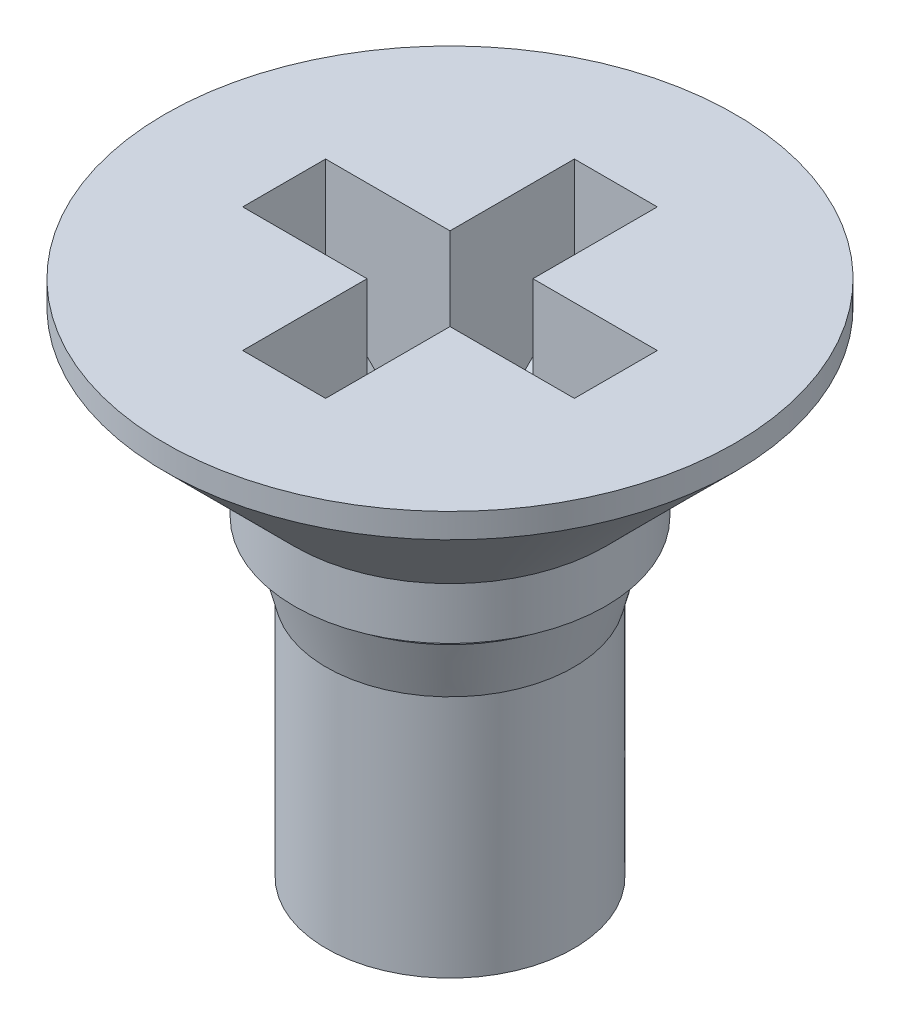
SolidWorks part; units mm, degrees
ref_plane "Vorderseite" through (0, 0, 0) normal (0, 0, 1) x (1, 0, 0)
ref_plane "Oben" through (0, 0, 0) normal (0, 1, 0) x (1, 0, 0)
ref_plane "Rechts" through (0, 0, 0) normal (1, 0, 0) x (0, 0, -1)
sketch "Skizze1" plane through (0, 0, 0) normal (0, 0, 1) x (1, 0, 0)
  line L0 (0, 0) -> (2.75, 0)
  line L1 (2.75, 0) -> (2.75, -0.2375)
  line L2 (2.75, -0.2375) -> (1.5, -1.4875)
  line L3 (1.3375, -1.9875) -> (1.3375, -2.1126)
  line L4 (1.3375, -2.1126) -> (1.1935, -2.65)
  line L5 (1.1935, -2.65) -> (1.1935, -8)
  line L6 (1.1935, -8) -> (0, -8)
  line L7 (0, 0) -> (0, -8) construction
  line L8 (0, 0) -> (0, -8)
  line L10 (1.5, -1.4875) -> (1.5, -1.9875)
  line L12 (1.5, -1.9875) -> (1.3375, -1.9875)
  point P3 (1.3375, -1.65)
  dimension "D1" = 45
  dimension "D2" = 15
  dimension "K" = 1.65
  dimension "DA" = 5.5
  dimension "DK" = 2.387
  dimension "L" = 8
  dimension "DG" = 3
  dimension "A" = 1
  dimension "DF" = 2.675
  dimension "P" = 0.5
revolve "Basis-Rotation" add sketch "Skizze1" angle 360 about L7
sketch "Skizze2" plane through (0, 0, 0) normal (0, 0, 1) x (1, 0, 0)
  line L0 (0, -2.1) -> (0, 0) construction
  line L1 (0, 0) -> (0, -8) construction
  line L2 (-0.55, -2.1) -> (0.55, -2.1)
  line L3 (1.6, 0) -> (1.6, -1.05)
  line L4 (1.6, -1.05) -> (0.55, -2.1)
  line L5 (1.6, 0) -> (-1.6, 0)
  line L6 (-1.6, -1.05) -> (-0.55, -2.1)
  line L7 (-1.6, 0) -> (-1.6, -1.05)
  line L8 (0, -1.05) -> (1.6, -1.05) construction
  line L9 (2.75, 0) -> (-2.75, 0) construction
  line L11 (1.5, -1.4875) -> (2.75, -0.2375) construction
  point P11 (0, 0)
  dimension "M" = 3.2
  dimension "T" = 2.1
extrude "Kreuzschlitz1 H" cut sketch "Skizze2" against normal blind 0.4 and the other way blind 0.4
sketch "Skizze3" plane through (0, 0, 0) normal (1, 0, 0) x (0, 0, -1)
  line L0 (0, -2.1) -> (0, 0) construction
  line L2 (-0.55, -2.1) -> (0.55, -2.1)
  line L3 (1.6, 0) -> (1.6, -1.05)
  line L4 (1.6, -1.05) -> (0.55, -2.1)
  line L5 (1.6, 0) -> (-1.6, 0)
  line L6 (-1.6, -1.05) -> (-0.55, -2.1)
  line L7 (-1.6, 0) -> (-1.6, -1.05)
  line L8 (0, -1.05) -> (1.6, -1.05) construction
  point P11 (0, 0)
extrude "Kreuzschlitz2 H" cut sketch "Skizze3" against normal blind 0.4 and the other way blind 0.4
sketch "Skizze4" plane through (2.4522, 0, -1.8507) normal (0, 1, 0) x (-1, 0, 0)
  line L0 (7.3522, 1.8507) -> (-2.4478, 1.8507) construction
  line L1 (2.4522, -3.0493) -> (2.4522, 6.7507) construction
  line L2 (-2.4478, 1.0342) -> (-2.4478, 2.6672)
  line L3 (-2.4478, 1.0342) -> (0.0059, 1.0342)
  line L4 (0.0059, 1.0342) -> (0.8191, 0.6258)
  line L5 (1.2273, 0.2176) -> (-1.0126, -1.6141)
  line L6 (0.8191, 0.6258) -> (-1.0126, -1.6141)
  line L7 (1.6357, -0.5956) -> (1.2273, 0.2176)
  line L8 (1.6357, -3.0493) -> (1.6357, -0.5956)
  line L9 (1.6357, -3.0493) -> (3.2687, -3.0493)
  line L10 (3.2687, -3.0493) -> (3.2687, -0.5956)
  line L11 (3.2687, -0.5956) -> (3.6772, 0.2176)
  line L12 (2.4522, 1.8507) -> (-1.0126, -1.6141) construction
  line L13 (4.0854, 0.6258) -> (5.917, -1.6141)
  line L14 (3.6772, 0.2176) -> (5.917, -1.6141)
  line L15 (4.8986, 1.0342) -> (4.0854, 0.6258)
  line L16 (7.3522, 1.0342) -> (4.8986, 1.0342)
  line L17 (7.3522, 1.0342) -> (7.3522, 2.6672)
  line L18 (7.3522, 2.6672) -> (4.8986, 2.6672)
  line L19 (4.8986, 2.6672) -> (4.0854, 3.0757)
  line L20 (3.6772, 3.4839) -> (5.917, 5.3156)
  line L21 (4.0854, 3.0757) -> (5.917, 5.3156)
  line L22 (3.2687, 4.2971) -> (3.6772, 3.4839)
  line L23 (3.2687, 6.7507) -> (3.2687, 4.2971)
  line L24 (1.6357, 6.7507) -> (3.2687, 6.7507)
  line L25 (1.6357, 6.7507) -> (1.6357, 4.2971)
  line L26 (1.6357, 4.2971) -> (1.2273, 3.4839)
  line L27 (0.8191, 3.0757) -> (-1.0126, 5.3156)
  line L28 (1.2273, 3.4839) -> (-1.0126, 5.3156)
  line L29 (0.0059, 2.6672) -> (0.8191, 3.0757)
  line L30 (-2.4478, 2.6672) -> (0.0059, 2.6672)
  circle A0 centre (2.4522, 1.8507) radius 4.9 construction
  circle A1 centre (2.4522, 1.8507) radius 2.0415 construction
  circle A2 centre (2.4522, 1.8507) radius 2.579 construction
  dimension "X2" = 4.083
  dimension "X1" = 5.158
  dimension "M" = 9.8
  dimension "D3" = 5.725
  dimension "X3" = 1.633
sketch "Sketch1" plane through (0, -8, 0) normal (0, -1, 0) x (1, 0, 0)
  circle A0 centre (0, 0) radius 1.1935
extrude "Boss-Extrude1" add sketch "Sketch1" along normal blind 2
sketch "Sketch2" plane through (0, 0, 0) normal (1, 0, 0) x (0, 0, -1)
  line L0 (1.1935, -10) -> (1.1935, -2.65) construction
  line L1 (-1.1935, -10) -> (1.1935, -10)
  line L2 (-1.1935, -10) -> (-1.1935, -5)
  line L3 (-1.1935, -5) -> (1.1935, -5)
  line L4 (1.1935, -10) -> (1.1935, -5)
  dimension "D1" = 5
extrude "Cut-Extrude1" cut sketch "Sketch2" against normal blind 2 and the other way blind 2
